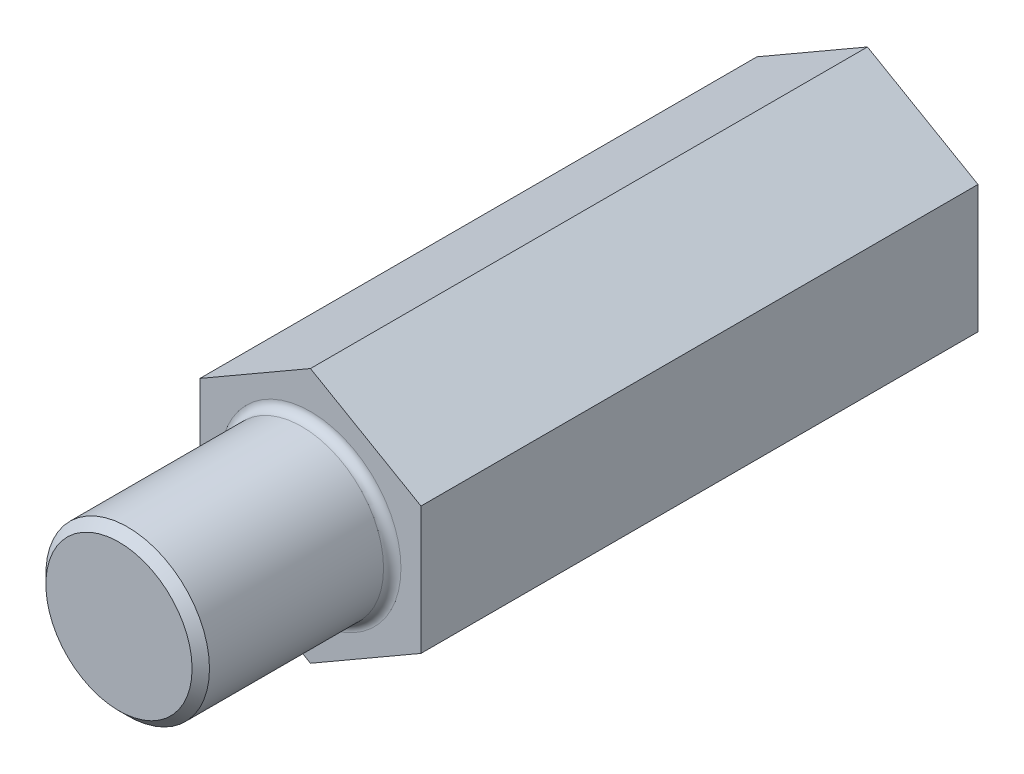
SolidWorks part; units mm, degrees
ref_plane "Front Plane" through (0, 0, 0) normal (0, 0, 1) x (1, 0, 0)
ref_plane "Top Plane" through (0, 0, 0) normal (0, 1, 0) x (1, 0, 0)
ref_plane "Right Plane" through (0, 0, 0) normal (1, 0, 0) x (0, 0, -1)
sketch "Sketch1" plane through (0, 0, 0) normal (0, 0, 1) x (1, 0, 0)
  line L1 (0, 7.3323) -> (-6.35, 3.6662)
  line L2 (-6.35, 3.6662) -> (-6.35, -3.6662)
  line L3 (-6.35, -3.6662) -> (0, -7.3323)
  line L4 (0, -7.3323) -> (6.35, -3.6662)
  line L5 (6.35, -3.6662) -> (6.35, 3.6662)
  line L6 (6.35, 3.6662) -> (0, 7.3323)
  circle A0 centre (0, 0) radius 6.35 construction
  dimension "D1" = 12.7
extrude "Boss-Extrude1" add sketch "Sketch1" along normal blind 43
sketch "Sketch4" plane through (0, 0, 43) normal (0, 0, 1) x (1, 0, 0)
  circle A0 centre (0, 0) radius 4.7
  circle A1 centre (0, 0) radius 10.2077
  dimension "D1" = 9.4
extrude "Cut-Extrude3" cut sketch "Sketch4" against normal blind 11
chamfer "Chamfer3" distance 0.5 angle 45 1 edges at (4.7, 0, 43)
fillet "Fillet2" radius 0.5 1 edges at (4.7, 0, 32)
hole_wizard "Ø1.0mm Dowel Hole1" positions "Sketch5" profile "Sketch6" hole size "Ø1.0" standard "ANSI Metric"
sketch "Sketch5" plane through (0, 0, 0) normal (0, 0, -1) x (-1, 0, 0)
  point P0 (0, 0)
sketch "Sketch6" plane through (0, 0, 0) normal (1, 0, 0) x (0, 1, 0)
  line L0 (0, 0) -> (0, 14.9077)
  line L1 (0, 14.9077) -> (3.175, 13)
  line L2 (3.175, 13) -> (3.175, 0)
  line L5 (3.175, 0) -> (0, 0)
  line L10 (0, 14.9077) -> (-3.175, 13) construction
  line L11 (0, -6.35) -> (0, 107.95) construction
  dimension "Hole Dia." = 6.35
  dimension "Hole Depth" = 13
  dimension "Drill Angle" = 118
chamfer "Chamfer4" distance 0.5 1 edges at (-3.175, 0, 0)
